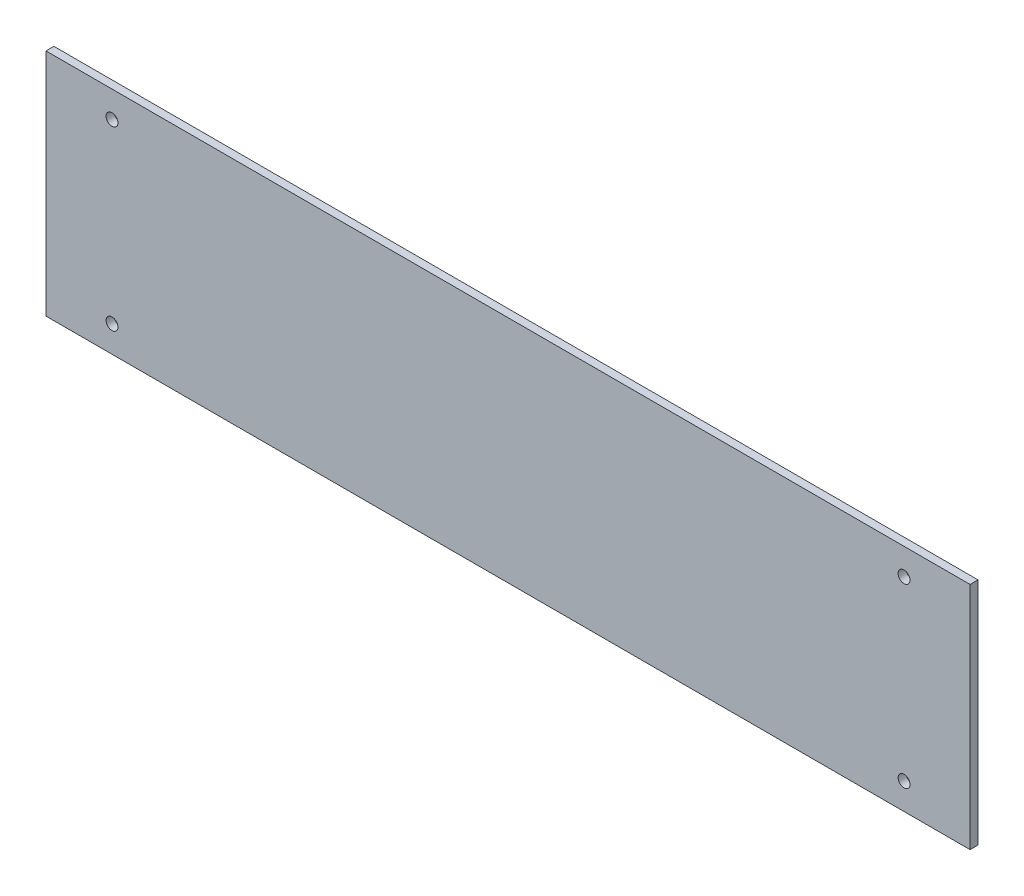
SolidWorks part; units mm, degrees
ref_plane "Plan de face" through (0, 0, 0) normal (0, 0, 1) x (1, 0, 0)
ref_plane "Plan de dessus" through (0, 0, 0) normal (0, 1, 0) x (1, 0, 0)
ref_plane "Plan de droite" through (0, 0, 0) normal (1, 0, 0) x (0, 0, -1)
sketch "Esquisse1" plane through (0, 0, 0) normal (0, 0, 1) x (1, 0, 0)
  line L0 (-175, 43.5) -> (175, -43.5) construction
  line L1 (-175, 43.5) -> (175, 43.5)
  line L2 (-175, 43.5) -> (-175, -43.5)
  line L3 (-175, -43.5) -> (175, -43.5)
  line L4 (175, 43.5) -> (175, -43.5)
  point P4 (0, 0)
  dimension "D1" = 350
  dimension "D2" = 87
extrude "Boss.-Extru.1" add sketch "Esquisse1" along normal blind 3
sketch "Esquisse2" plane through (0, 0, 3) normal (0, 0, 1) x (1, 0, 0)
  line L0 (-175, 33.5) -> (175, 33.5) construction
  line L1 (-175, 43.5) -> (-175, -43.5) construction
  line L2 (175, -43.5) -> (175, 43.5) construction
  line L3 (0, 33.5) -> (0, 43.5) construction
  line L4 (175, -33.5) -> (-175, -33.5) construction
  line L5 (175, 43.5) -> (-175, 43.5) construction
  line L6 (0, -33.5) -> (0, -43.5) construction
  line L7 (-175, -43.5) -> (175, -43.5) construction
  circle A0 centre (-150, 33.5) radius 2.25
  circle A1 centre (-150, -33.5) radius 2.25
  circle A2 centre (150, 33.5) radius 2.25
  circle A3 centre (150, -33.5) radius 2.25
  point P24 (0, 0)
  point P25 (0, 0)
  point P26 (0, 0)
  dimension "D2" = 4.5
  dimension "D3" = 25
  dimension "D1" = 10
extrude "Enlèv. mat.-Extru.1" cut sketch "Esquisse2" against normal up to next
